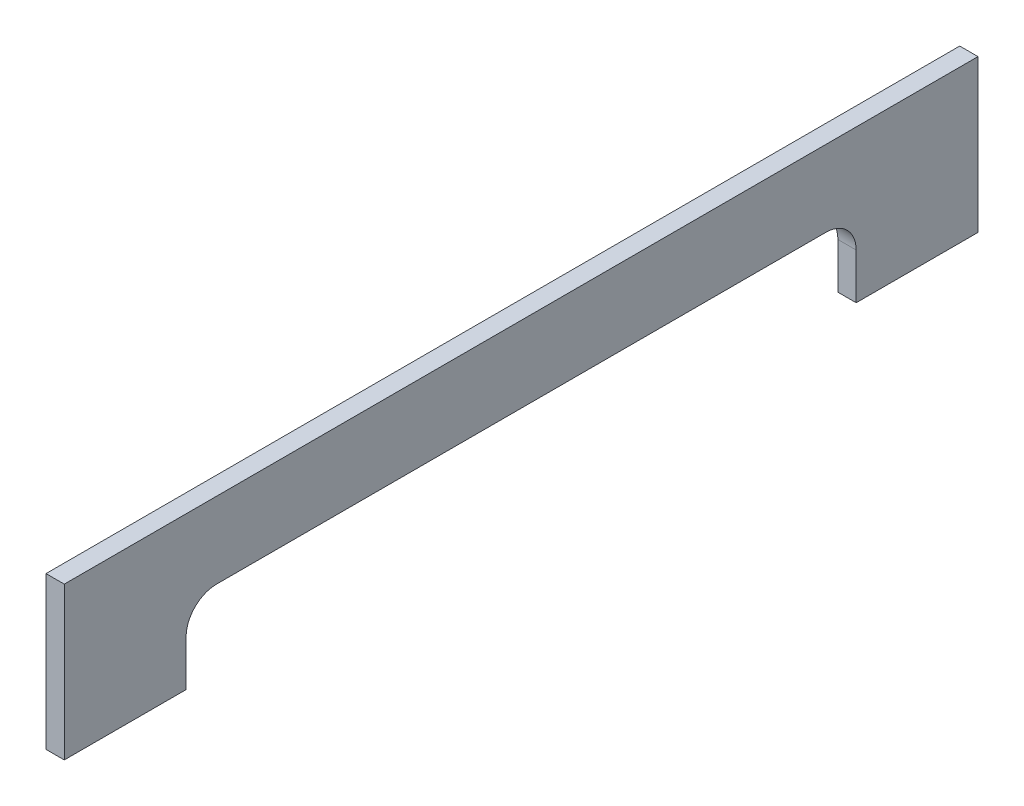
SolidWorks part; units mm, degrees
material "CA"
ref_plane "Front Plane" through (0, 0, 0) normal (0, 0, 1) x (1, 0, 0)
ref_plane "Top Plane" through (0, 0, 0) normal (0, 1, 0) x (1, 0, 0)
ref_plane "Right Plane" through (0, 0, 0) normal (1, 0, 0) x (0, 0, -1)
sketch "Sketch1" plane through (0, 0, 0) normal (1, 0, 0) x (0, 0, -1)
  line L1 (-150, 25) -> (150, 25)
  line L2 (-150, 25) -> (-150, -25)
  line L3 (-150, -25) -> (150, -25)
  line L4 (150, 25) -> (150, -25)
  point P4 (0, 25)
  point P5 (-150, 0)
  dimension "D1" = 300
  dimension "D2" = 50
extrude "Boss-Extrude1" add sketch "Sketch1" along normal blind 6
sketch "Sketch2" plane through (6, 0, 0) normal (1, 0, 0) x (0, 0, -1)
  line L0 (-150, -25) -> (150, -25) construction
  line L1 (-110, 0) -> (110, 0)
  line L2 (-110, 0) -> (-110, -25)
  line L3 (-110, -25) -> (110, -25)
  line L4 (110, 0) -> (110, -25)
  line L5 (-150, 25) -> (-150, -25) construction
  line L6 (150, -25) -> (150, 25) construction
  line L7 (150, 25) -> (-150, 25) construction
  dimension "D1" = 40
  dimension "D2" = 40
  dimension "D3" = 25
extrude "Cut-Extrude1" cut sketch "Sketch2" against normal blind 10
fillet "Fillet1" radius 10 2 edges at (3, 0, -110) (3, 0, 110)
